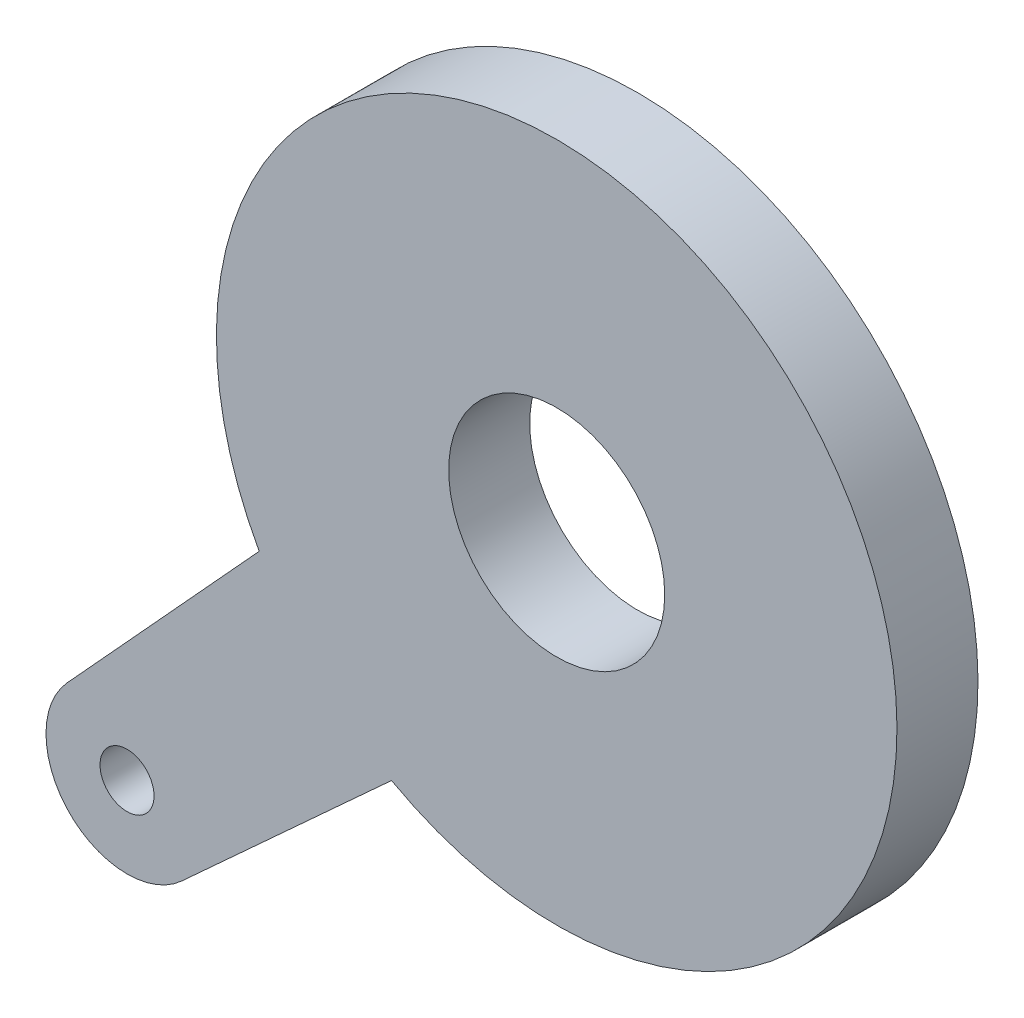
SolidWorks part; units mm, degrees
ref_plane "Front Plane" through (0, 0, 0) normal (0, 0, 1) x (1, 0, 0)
ref_plane "Top Plane" through (0, 0, 0) normal (0, 1, 0) x (1, 0, 0)
ref_plane "Right Plane" through (0, 0, 0) normal (1, 0, 0) x (0, 0, -1)
sketch "Sketch1" plane through (0, 0, 0) normal (0, 0, 1) x (1, 0, 0)
  line L0 (0, 20.4518) -> (0, -35.967) construction
  line L1 (0, 0) -> (-26.4886, -26.4886) construction
  line L2 (-11.0162, -6.1159) -> (-18.1234, -13.885)
  line L4 (-6.1159, -11.0162) -> (-13.885, -18.1234)
  arc A0 (-6.1159, -11.0162) -> (-11.0162, -6.1159) centre (0, 0) ccw
  circle A1 centre (0, 0) radius 4
  arc A2 (-18.1234, -13.885) -> (-13.885, -18.1234) centre (-15.9099, -15.9099) ccw
  circle A3 centre (-15.9099, -15.9099) radius 1
  dimension "D1" = 25.2
  dimension "D2" = 8
  dimension "D4" = 6
  dimension "D5" = 2
  dimension "D3" = 45
  dimension "D6" = 22.5
extrude "Boss-Extrude1" add sketch "Sketch1" along normal blind 3
